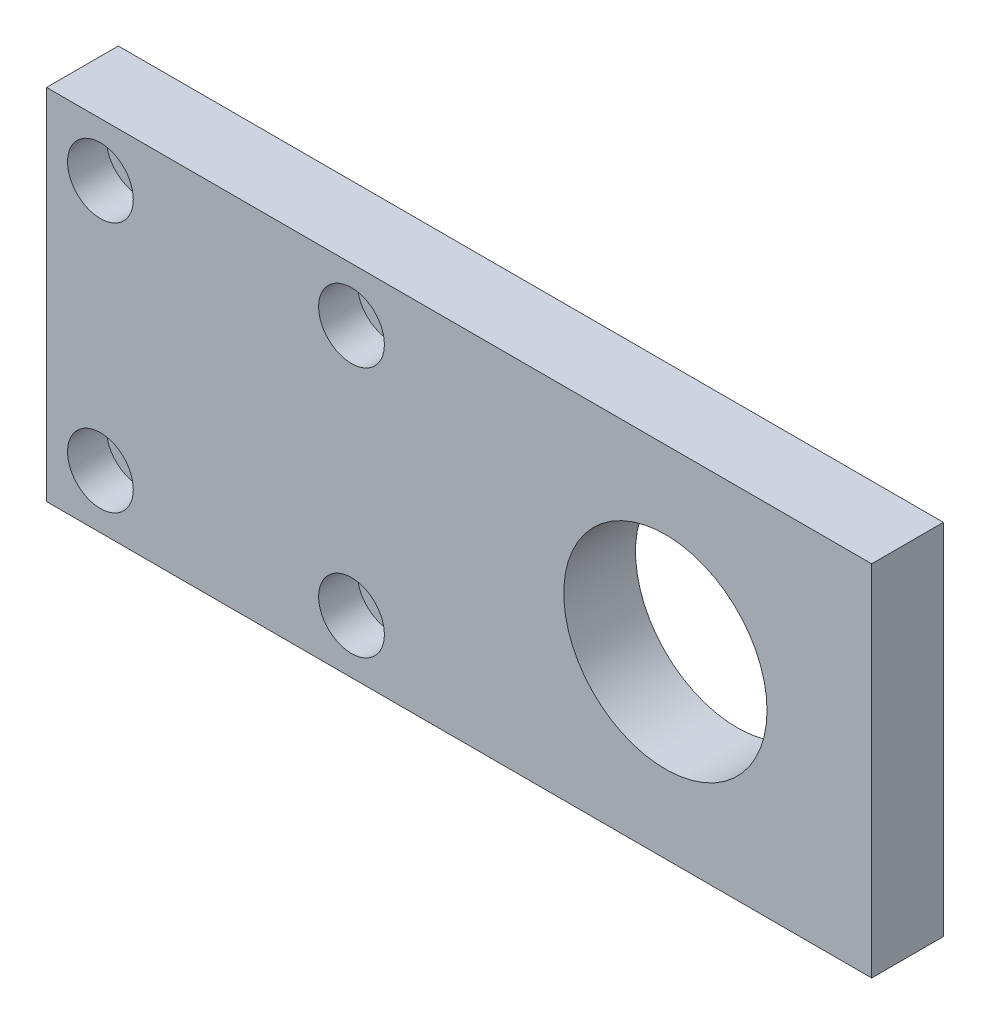
SolidWorks part; units mm, degrees
material "1.0037 (S235JR)"
ref_plane "Płaszczyzna przednia" through (0, 0, 0) normal (0, 0, 1) x (1, 0, 0)
ref_plane "Płaszczyzna górna" through (0, 0, 0) normal (0, 1, 0) x (1, 0, 0)
ref_plane "Płaszczyzna prawa" through (0, 0, 0) normal (1, 0, 0) x (0, 0, -1)
sketch "Szkic1" plane through (0, 0, 0) normal (0, 0, 1) x (1, 0, 0)
  line L0 (-70, 300) -> (-10, 300) construction
  line L1 (-70, 360) -> (68, 360)
  line L2 (-70, 360) -> (-70, 300)
  line L3 (-70, 300) -> (68, 300)
  line L4 (68, 360) -> (68, 300)
  circle A0 centre (33.5, 330) radius 17
  circle A1 centre (33.5, 330) radius 16 construction
  dimension "D1" = 34
  dimension "D2" = 138
extrude "Dodanie-wyciągnięcie1" add sketch "Szkic1" along normal blind 12
hole_wizard "Pogłębienie walcowe pod M5 Wkręt do części metalowych z łbem sześciokątnym1" positions "Szkic3" profile "Szkic2" counterbore size "M5" standard "Ansi Metric" end condition through all
sketch "Szkic3" plane through (0, 0, 12) normal (0, 0, 1) x (1, 0, 0)
  line L1 (-61, 351) -> (-19, 351)
  line L2 (-61, 351) -> (-61, 309)
  line L3 (-61, 309) -> (-19, 309)
  line L4 (-19, 351) -> (-19, 309)
  line L5 (68, 360) -> (-70, 360) construction
  line L6 (-70, 360) -> (-70, 300) construction
  point P0 (-61, 351)
  point P2 (-19, 351)
  point P4 (-61, 309)
  point P6 (-19, 309)
  dimension "D1" = 9
  dimension "D2" = 9
  dimension "D3" = 42
  dimension "D4" = 42
sketch "Szkic2" plane through (-61, 351, 12) normal (1, 0, 0) x (0, -1, 0)
  line L0 (0, 0) -> (0, 12)
  line L1 (0, 12) -> (2.75, 12)
  line L3 (2.75, 12) -> (2.75, 6.5)
  line L4 (2.75, 6.5) -> (5.5, 6.5)
  line L5 (5.5, 6.5) -> (5.5, 0)
  line L7 (5.5, 0) -> (0, 0)
  line L11 (0, -6.35) -> (0, 107.95) construction
  dimension "Średnica otworu na wylot" = 5.5
  dimension "Głębokość otworu na wylot" = 12
  dimension "Średnica pogłębienia walcowego" = 11
  dimension "Głębokość pogłębienia walcowego" = 6.5
ref_plane "Płaszczyzna1" through (0, 330, 0) normal (0, 1, 0) x (1, 0, 0)
equation "\"D2@Szkic3\"=\"D1@Szkic3\""
equation "\"D4@Szkic3\"=\"D3@Szkic3\""
